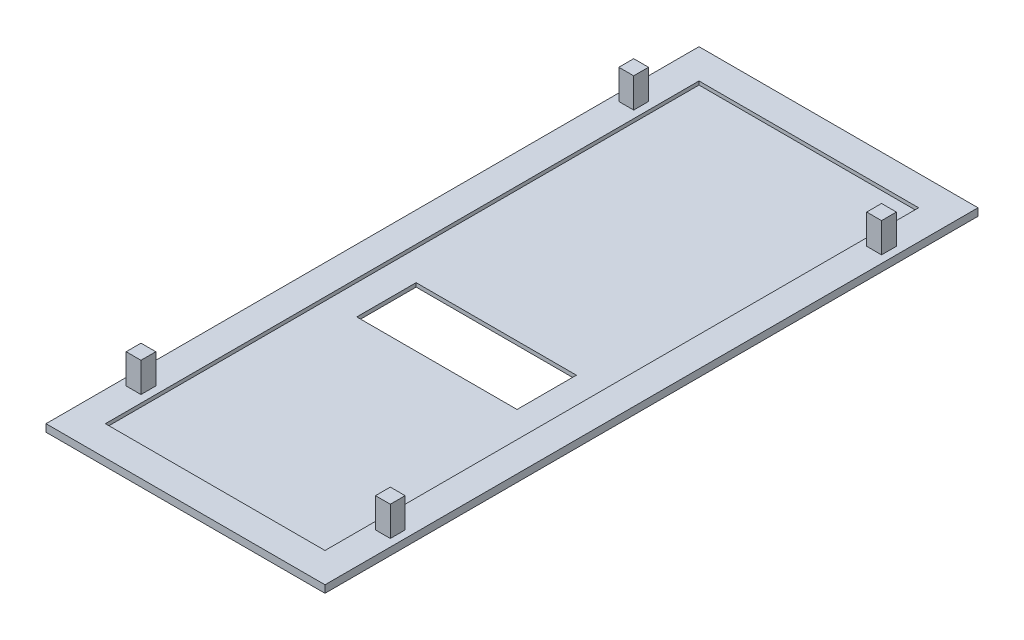
SolidWorks part; units mm, degrees
ref_plane "Front Plane" through (0, 0, 0) normal (0, 0, 1) x (1, 0, 0)
ref_plane "Top Plane" through (0, 0, 0) normal (0, 1, 0) x (1, 0, 0)
ref_plane "Right Plane" through (0, 0, 0) normal (1, 0, 0) x (0, 0, -1)
sketch "Sketch1" plane through (0, 0, 0) normal (0, 1, 0) x (1, 0, 0)
  line L1 (0, 0) -> (47, 0)
  line L2 (0, 0) -> (0, 110)
  line L3 (0, 110) -> (47, 110)
  line L4 (47, 0) -> (47, 110)
  dimension "D1" = 110
  dimension "D2" = 47
extrude "Boss-Extrude1" add sketch "Sketch1" along normal blind 1.25
sketch "Sketch2" plane through (0, 1.25, 0) normal (0, 1, 0) x (1, 0, 0)
  line L0 (47, 0) -> (47, 110) construction
  line L1 (43.25, 97.5) -> (45.75, 97.5)
  line L2 (43.25, 97.5) -> (43.25, 95)
  line L3 (43.25, 95) -> (45.75, 95)
  line L4 (45.75, 97.5) -> (45.75, 95)
  line L5 (47, 110) -> (0, 110) construction
  line L6 (0, 0) -> (47, 0) construction
  line L7 (45.75, 14.75) -> (43.25, 14.75)
  line L8 (45.75, 14.75) -> (45.75, 12.25)
  line L9 (45.75, 12.25) -> (43.25, 12.25)
  line L10 (43.25, 14.75) -> (43.25, 12.25)
  line L11 (0, 110) -> (0, 0) construction
  line L12 (1.25, 12.25) -> (3.75, 12.25)
  line L13 (1.25, 12.25) -> (1.25, 14.75)
  line L14 (1.25, 14.75) -> (3.75, 14.75)
  line L15 (3.75, 12.25) -> (3.75, 14.75)
  line L17 (1.25, 97.75) -> (3.75, 97.75)
  line L18 (1.25, 97.75) -> (1.25, 95.25)
  line L19 (1.25, 95.25) -> (3.75, 95.25)
  line L20 (3.75, 97.75) -> (3.75, 95.25)
  point P12 (44.5, 12.25)
  dimension "D1" = 2.5
  dimension "D2" = 2.5
  dimension "D3" = 1.25
  dimension "D4" = 12.5
  dimension "D5" = 2.5
  dimension "D6" = 2.5
  dimension "D7" = 1.25
  dimension "D8" = 12.25
  dimension "D9" = 2.5
  dimension "D10" = 2.5
  dimension "D11" = 1.25
  dimension "D12" = 12.25
  dimension "D13" = 2.5
  dimension "D14" = 2.5
  dimension "D15" = 1.25
  dimension "D16" = 12.25
extrude "Boss-Extrude2" add sketch "Sketch2" along normal blind 5
sketch "Sketch3" plane through (0, 1.25, 0) normal (0, 1, 0) x (1, 0, 0)
  line L0 (0, 0) -> (47, 0) construction
  line L1 (10, 52.35) -> (37, 52.35)
  line L2 (10, 52.35) -> (10, 42.35)
  line L3 (10, 42.35) -> (37, 42.35)
  line L4 (37, 52.35) -> (37, 42.35)
  line L5 (0, 110) -> (0, 0) construction
  line L6 (47, 0) -> (47, 110) construction
  dimension "D1" = 42.35
  dimension "D2" = 10
  dimension "D3" = 10
  dimension "D4" = 10
extrude "Cut-Extrude1" cut sketch "Sketch3" against normal blind 5
sketch "Sketch6" plane through (0, 1.25, 0) normal (0, 1, 0) x (1, 0, 0)
  line L0 (0, 110) -> (0, 0) construction
  line L1 (5, 105) -> (42, 105)
  line L2 (5, 105) -> (5, 5)
  line L3 (5, 5) -> (42, 5)
  line L4 (42, 105) -> (42, 5)
  line L5 (47, 110) -> (0, 110) construction
  line L6 (47, 0) -> (47, 110) construction
  line L7 (0, 0) -> (47, 0) construction
  dimension "D1" = 5
  dimension "D2" = 5
  dimension "D3" = 5
  dimension "D4" = 5
extrude "Cut-Extrude2" cut sketch "Sketch6" against normal blind 0.6
